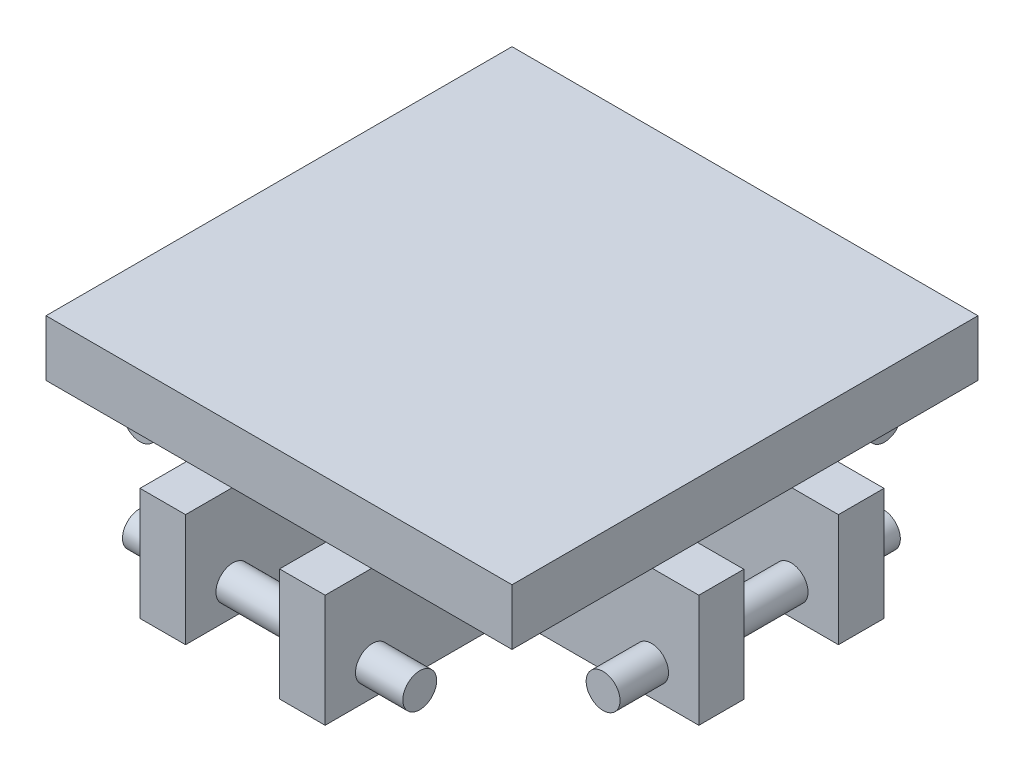
SolidWorks part; units mm, degrees
ref_plane "Front Plane" through (0, 0, 0) normal (0, 0, 1) x (1, 0, 0)
ref_plane "Top Plane" through (0, 0, 0) normal (0, 1, 0) x (1, 0, 0)
ref_plane "Right Plane" through (0, 0, 0) normal (1, 0, 0) x (0, 0, -1)
sketch "Sketch1" plane through (0, 0, 0) normal (0, 1, 0) x (1, 0, 0)
  line L1 (-40.432, 34.9347) -> (39.368, 34.9347)
  line L2 (-40.432, 34.9347) -> (-40.432, -44.8653)
  line L3 (-40.432, -44.8653) -> (39.368, -44.8653)
  line L4 (39.368, 34.9347) -> (39.368, -44.8653)
  dimension "D1" = 79.8
  dimension "D2" = 79.8
extrude "Boss-Extrude1" add sketch "Sketch1" along normal blind 9.6 contours L4 L3 L2 L1
sketch "Sketch3" plane through (0, 0, 0) normal (0, -1, 0) x (1, 0, 0)
  line L0 (-46.5398, 20.8153) -> (47.318, 20.8153)
  line L1 (-16.382, 20.8153) -> (15.318, 20.8153)
  line L2 (-16.382, 20.8153) -> (-16.382, -10.8847)
  line L3 (-16.382, -10.8847) -> (15.318, -10.8847)
  line L4 (15.318, 20.8153) -> (15.318, -10.8847)
  line L9 (-48.382, -3.0847) -> (47.318, -3.0847)
  line L10 (-48.382, -3.0847) -> (-48.382, -10.8847)
  line L11 (-48.382, -10.8847) -> (47.318, -10.8847)
  line L12 (47.318, -3.0847) -> (47.318, -10.8847)
  line L13 (-46.5398, 20.8153) -> (-46.5398, 13.1153)
  line L14 (-46.5398, 13.1153) -> (47.318, 13.1153)
  line L15 (47.318, 20.8153) -> (47.318, 13.1153)
  line L24 (39.368, -34.9347) -> (39.368, 44.8653) construction
  line L25 (-40.432, -34.9347) -> (39.368, -34.9347) construction
  line L26 (7.518, 25.419) -> (7.518, -6.281)
  line L27 (-16.382, 52.8153) -> (-8.582, 52.8153)
  line L28 (-16.382, 52.8153) -> (-16.382, -42.8847)
  line L29 (-16.382, -42.8847) -> (-8.582, -42.8847)
  line L30 (-8.582, 52.8153) -> (-8.582, -42.8847)
  line L31 (7.518, 52.8153) -> (15.318, 52.8153)
  line L32 (7.518, 52.8153) -> (7.518, -42.8847)
  line L33 (7.518, -42.8847) -> (15.318, -42.8847)
  line L34 (15.318, 52.8153) -> (15.318, -42.8847)
  dimension "D1" = 31.7
  dimension "D2" = 31.7
  dimension "D3" = 95.7
  dimension "D4" = 7.8
  dimension "D5" = 32
  dimension "D6" = 95.7
  dimension "D7" = 32
  dimension "D8" = 95.7
  dimension "D9" = 16.2
  dimension "D10" = 7.8
  dimension "D11" = 7.8
  dimension "D12" = 32
  dimension "D13" = 24.05
  dimension "D14" = 24.05
extrude "Boss-Extrude2" add sketch "Sketch3" along normal blind 19.3 contours L1 L26 L14 L4 | L1 L30 L14 L26 | L14 L30 L9 L26 | L30 L0 L2 L14 | L11 L14 L2 L0 | L30 L12 L28 L0 | L34 L12 L32 L1 | L34 L31 L32 L12 | L30 L27 L28 L12 | L13 L14 L11 L0 | L15 L0 L9 L14 | L4 L14 L9 L0 | L14 L26 L9 L4 | L30 L14 L2 L9 | L30 L9 L2 L3 | L11 L2 L9 | L10 L11 L9 | L9 L30 L11 L26 | L9 L26 L11 L4 | L34 L11 L32 L10 | L4 L11 L9 | L12 L9 L11 | L34 L10 L32 L33 | L30 L3 L28 L10 | L30 L10 L28 L29
sketch "Sketch4" plane through (0, 0, -3.0847) normal (0, 0, 1) x (1, 0, 0)
  line L0 (-48.382, -19.3) -> (-48.382, 0) construction
  line L1 (-48.382, -19.3) -> (-16.382, -19.3) construction
  circle A0 centre (-40.282, -14.1) radius 2.9
  point P2 (0, 0)
  point P3 (0, 0)
  point P4 (0, 0)
  point P5 (0, 0)
  dimension "D1" = 8.1
  dimension "D2" = 5.8
  dimension "D3" = 5.2
extrude "Boss-Extrude3" add sketch "Sketch4" along normal blind 32 and the other way blind 16
sketch "Sketch5" plane through (-8.582, 0, 0) normal (1, 0, 0) x (0, 0, -1)
  line L0 (-52.8153, -19.3) -> (-20.8153, -19.3) construction
  line L1 (-52.8153, -19.3) -> (-52.8153, 0) construction
  circle A0 centre (-44.7153, -14.1) radius 2.9
  dimension "D2" = 5.8
  dimension "D1" = 5.2
  dimension "D3" = 8.1
extrude "Boss-Extrude4" add sketch "Sketch5" along normal blind 32 and the other way blind 16
sketch "Sketch6" plane through (0, 0, 13.1153) normal (0, 0, -1) x (-1, 0, 0)
  line L0 (-47.318, -19.3) -> (-47.318, 0) construction
  line L1 (-15.318, -19.3) -> (-47.318, -19.3) construction
  circle A0 centre (-39.218, -14.1) radius 2.9
  dimension "D1" = 5.8
  dimension "D2" = 8.1
  dimension "D3" = 5.2
extrude "Boss-Extrude5" add sketch "Sketch6" along normal blind 32 and the other way blind 16
sketch "Sketch7" plane through (7.518, 0, 0) normal (-1, 0, 0) x (0, 0, 1)
  line L0 (-10.8847, -19.3) -> (-42.8847, -19.3) construction
  line L2 (-42.8847, -19.3) -> (-42.8847, 0) construction
  circle A0 centre (-34.7847, -14.1) radius 2.9
  point P6 (-40.0698, -13.4886)
  point P7 (-46.5451, -13.2964)
  point P8 (0, 0)
  point P9 (-42.8847, -13.6291)
  point P10 (0, 0)
  dimension "D1" = 5.8
  dimension "D2" = 5.2
  dimension "D3" = 8.1
extrude "Boss-Extrude6" add sketch "Sketch7" along normal blind 32 and the other way blind 16
